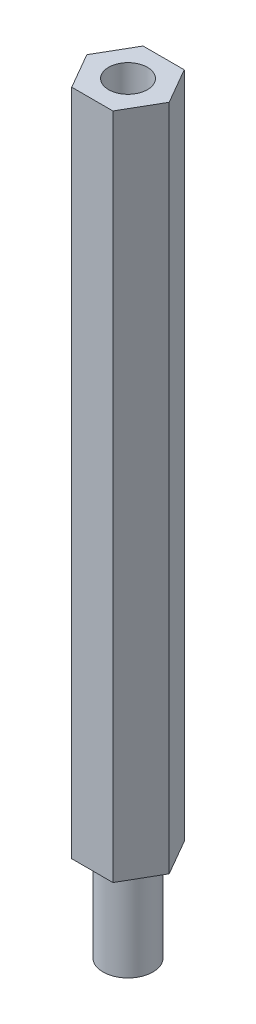
SolidWorks part; units mm, degrees
ref_plane "前视基准面" through (0, 0, 0) normal (0, 0, 1) x (1, 0, 0)
ref_plane "上视基准面" through (0, 0, 0) normal (0, 1, 0) x (1, 0, 0)
ref_plane "右视基准面" through (0, 0, 0) normal (1, 0, 0) x (0, 0, -1)
sketch "草图4" plane through (0, 0, 0) normal (0, 1, 0) x (1, 0, 0)
  line L0 (-12.7945, 0) -> (16.3015, 0) construction
  line L2 (1.325, -2.295) -> (2.65, 0)
  line L3 (2.65, 0) -> (1.325, 2.295)
  line L4 (1.325, 2.295) -> (-1.325, 2.295)
  line L5 (-1.325, 2.295) -> (-2.65, 0)
  line L6 (-2.65, 0) -> (-1.325, -2.295)
  line L7 (-1.325, -2.295) -> (1.325, -2.295)
  circle A0 centre (0, 0) radius 2.295 construction
  dimension "D1" = 5.3
extrude "凸台-拉伸1" add sketch "草图4" along normal blind 43
sketch "草图6" plane through (0, 0, 0) normal (0, -1, 0) x (-1, 0, 0)
  circle A0 centre (0, 0) radius 1.6
  dimension "D1" = 3.2
extrude "凸台-拉伸2" add sketch "草图6" along normal blind 6
cosmetic thread "装饰螺纹线1" parameters "D2"=2.5
sketch "草图7" plane through (0, 43, 0) normal (0, 1, 0) x (1, 0, 0)
  circle A0 centre (0, 0) radius 1.25
  dimension "D1" = 2.5
extrude "切除-拉伸1" cut sketch "草图7" against normal blind 5
cosmetic thread "装饰螺纹线2" parameters "D2"=3
